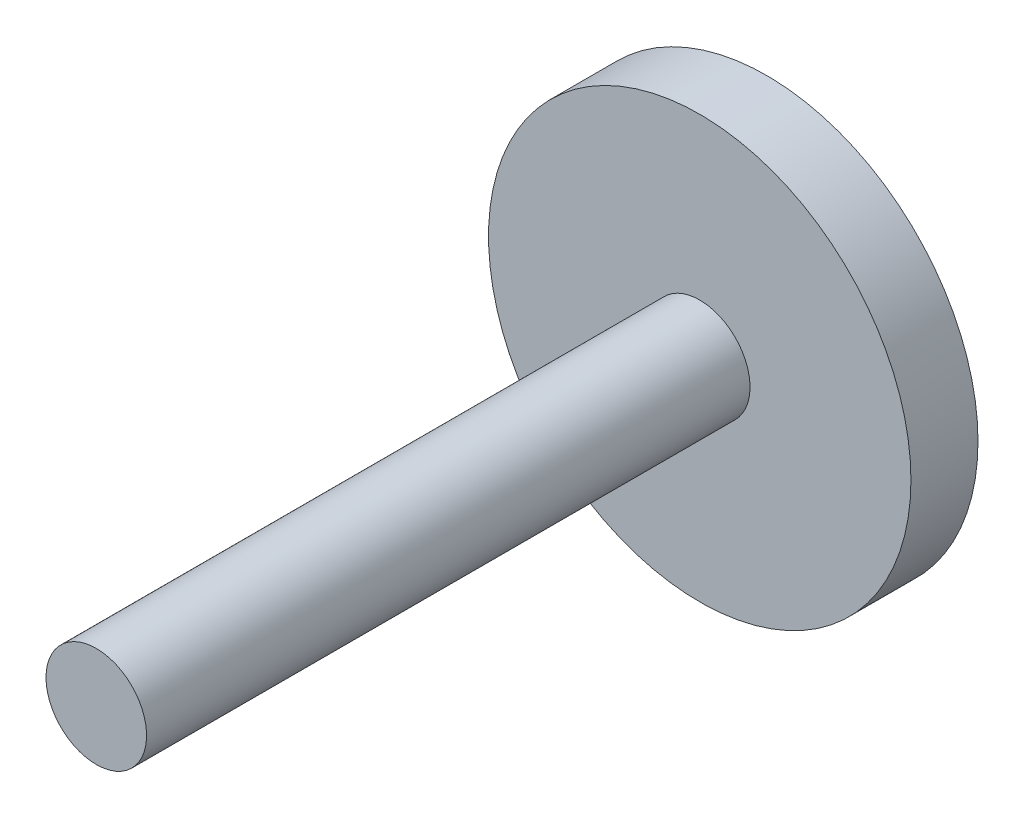
SolidWorks part; units mm, degrees
ref_plane "Front Plane" through (0, 0, 0) normal (0, 0, 1) x (1, 0, 0)
ref_plane "Top Plane" through (0, 0, 0) normal (0, 1, 0) x (1, 0, 0)
ref_plane "Right Plane" through (0, 0, 0) normal (1, 0, 0) x (0, 0, -1)
sketch "Sketch1" plane through (0, 0, 0) normal (0, 0, 1) x (1, 0, 0)
  circle A0 centre (0, 0) radius 31.5
  dimension "D1" = 63
extrude "Boss-Extrude1" add sketch "Sketch1" along normal blind 10
sketch "Sketch2" plane through (0, 0, 0) normal (0, 0, 1) x (1, 0, 0)
  circle A0 centre (0, 0) radius 7.5
  dimension "D1" = 15
extrude "Boss-Extrude2" add sketch "Sketch2" along normal blind 100
